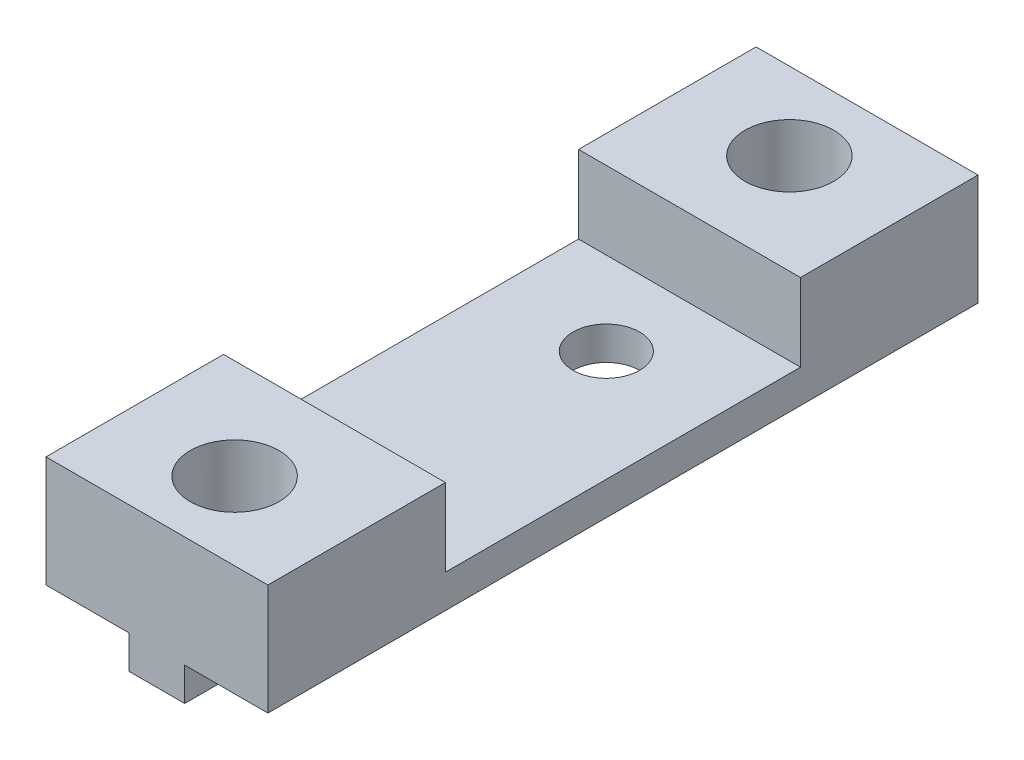
SolidWorks part; units mm, degrees
ref_plane "Front Plane" through (0, 0, 0) normal (0, 0, 1) x (1, 0, 0)
ref_plane "Top Plane" through (0, 0, 0) normal (0, 1, 0) x (1, 0, 0)
ref_plane "Right Plane" through (0, 0, 0) normal (1, 0, 0) x (0, 0, -1)
sketch "Sketch1" plane through (0, 0, 0) normal (0, 1, 0) x (1, 0, 0)
  line L1 (-10, -15) -> (10, -15)
  line L2 (-10, -15) -> (-10, 15)
  line L3 (-10, 15) -> (10, 15)
  line L4 (10, -15) -> (10, 15)
  line L5 (-10, -15) -> (10, 15) construction
  line L6 (-10, 15) -> (10, -15) construction
  point P0 (0, 0)
  dimension "D1" = 20
  dimension "D2" = 30
extrude "Boss-Extrude1" add sketch "Sketch1" along normal blind 3
sketch "Sketch2" plane through (0, 0, 0) normal (0, -1, 0) x (1, 0, 0)
  line L0 (10, -15) -> (-10, -15) construction
  line L1 (-2.5, -15) -> (2.5, -15)
  line L2 (-2.5, -15) -> (-2.5, -3)
  line L3 (-2.5, -3) -> (2.5, -3)
  line L4 (2.5, -15) -> (2.5, -3)
  line L5 (-2.5, -15) -> (2.5, -3) construction
  line L6 (-2.5, -3) -> (2.5, -15) construction
  point P0 (0, -9)
  dimension "D1" = 0
  dimension "D2" = 5
  dimension "D3" = 0
  dimension "D4" = 12
extrude "Boss-Extrude2" add sketch "Sketch2" along normal blind 3
sketch "Sketch3" plane through (0, 3, 0) normal (0, 1, 0) x (1, 0, 0)
  line L0 (10, 15) -> (-10, 15) construction
  circle A0 centre (0, 8) radius 4
  circle A1 centre (0, 8) radius 7
  dimension "D1" = 14
  dimension "D2" = 7
  dimension "D3" = 8
extrude "Boss-Extrude3" add sketch "Sketch3" along normal blind 7
sketch "Sketch4" plane through (0, 3, 0) normal (0, 1, 0) x (1, 0, 0)
  circle A1 centre (0, 8) radius 4
  circle A2 centre (0, 8) radius 4
  dimension "D1" = 0
extrude "Boss-Extrude4" add sketch "Sketch4" along normal blind 1
sketch "Sketch5" plane through (0, 3, 0) normal (0, 1, 0) x (1, 0, 0)
  line L0 (-10, -15) -> (10, -15) construction
  circle A0 centre (0, -8.5) radius 3
  dimension "D1" = 6
  dimension "D2" = 6.5
  dimension "D3" = 0
extrude "Cut-Extrude1" cut sketch "Sketch5" against normal through all both and the other way through all
chamfer "Chamfer1" [suppressed] distance 4 angle 45
sketch "Sketch6" plane through (0, 3, 0) normal (0, 1, 0) x (1, 0, 0)
  line L0 (10, -15) -> (10, 15) construction
  line L1 (-10, 15) -> (10, 15)
  line L2 (-10, 15) -> (-10, -1)
  line L3 (-10, -1) -> (10, -1)
  line L4 (10, 15) -> (10, -1)
  circle A0 centre (0, 8) radius 7 construction
  circle A1 centre (0, 8) radius 7
  circle A3 centre (0, 8) radius 4
  circle A4 centre (0, 8) radius 4
  line M6 (10, 15) -> (0, 15)
  circle M7 centre (0, 8) radius 7
  line M8 (0, 15) -> (-10, 15)
  line M9 (-10, 15) -> (-10, -15)
  line M11 (10, -15) -> (10, 15)
  dimension "D1" = 16
  dimension "D2" = 0
extrude "Boss-Extrude6" add sketch "Sketch6" along normal up to surface (7 mm away) contours A4 M7 | L3 M9 M11 M6 M7 M8 up to face at (0, 10, -1)
ref_plane "Plane1" through (0, 0, -8) normal (0, 0, 1) x (1, 0, 0)
ref_plane "Plane2" through (0, 0, 17) normal (0, 0, 1) x (1, 0, 0)
sketch "Sketch7" plane through (0, 0, 15) normal (0, 0, 1) x (1, 0, 0)
  line L4 (-10, 0) -> (10, 0)
  line L5 (10, 0) -> (10, 3)
  line L6 (10, 3) -> (-10, 3)
  line L7 (-10, 3) -> (-10, 0)
  line L8 (-10, 0) -> (10, 0)
  line L9 (10, 0) -> (10, 3)
  line L10 (10, 3) -> (-10, 3)
  line L11 (-10, 3) -> (-10, 0)
  dimension "D1" = 0
extrude "Boss-Extrude7" add sketch "Sketch7" along normal blind 19
mirror "Mirror3" about plane through (0, 0, 17) normal (0, 0, 1) of "Boss-Extrude6", "Boss-Extrude4", "Boss-Extrude3", "Boss-Extrude2", "Boss-Extrude1"
sketch "Sketch8" plane through (0, 0, 37) normal (0, 0, -1) x (-1, 0, 0)
  line L4 (2.5, 0) -> (-2.5, 0)
  line L5 (-2.5, 0) -> (-2.5, -3)
  line L6 (-2.5, -3) -> (2.5, -3)
  line L7 (2.5, -3) -> (2.5, 0)
  line L8 (2.5, 0) -> (-2.5, 0)
  line L9 (-2.5, 0) -> (-2.5, -3)
  line L10 (-2.5, -3) -> (2.5, -3)
  line L11 (2.5, -3) -> (2.5, 0)
  dimension "D1" = 0
extrude "Boss-Extrude8" add sketch "Sketch8" along normal blind 12
sketch "Sketch10" plane through (0, 4, 0) normal (0, 1, 0) x (1, 0, 0)
  circle A0 centre (0, 8) radius 4 construction
  circle A1 centre (0, -42) radius 4 construction
  circle A2 centre (0, 8) radius 4
  circle A3 centre (0, -42) radius 4
extrude "Cut-Extrude2" cut sketch "Sketch10" against normal blind 1.5
